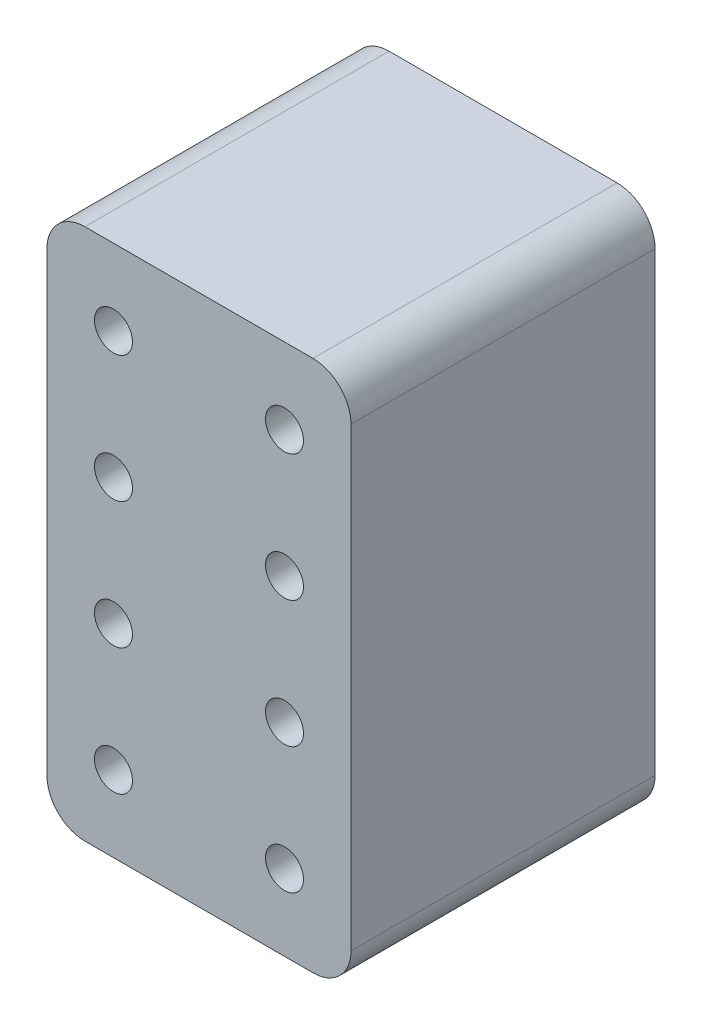
SolidWorks part; units mm, degrees
ref_plane "前视基准面" through (0, 0, 0) normal (0, 0, 1) x (1, 0, 0)
ref_plane "上视基准面" through (0, 0, 0) normal (0, 1, 0) x (1, 0, 0)
ref_plane "右视基准面" through (0, 0, 0) normal (1, 0, 0) x (0, 0, -1)
other "Configuration Table"
sketch "草图1" plane through (0, 0, 0) normal (0, 0, 1) x (1, 0, 0)
  line L0 (0, -55) -> (0, 55) construction
  line L1 (12, 28) -> (-12, 28)
  line L2 (16, 24) -> (16, -24)
  line L3 (12, -28) -> (-12, -28)
  line L4 (-16, 24) -> (-16, -24)
  line L5 (16, 28) -> (-16, -28) construction
  line L6 (16, -28) -> (-16, 28) construction
  circle A0 centre (9, 20) radius 2
  circle A1 centre (9, 6.6667) radius 2
  circle A2 centre (9, -6.6667) radius 2
  circle A3 centre (9, -20) radius 2
  circle A4 centre (-9, -20) radius 2
  circle A5 centre (-9, -6.6667) radius 2
  circle A6 centre (-9, 6.6667) radius 2
  circle A7 centre (-9, 20) radius 2
  arc A8 (-12, -28) -> (-16, -24) centre (-12, -24) cw
  arc A9 (16, -24) -> (12, -28) centre (12, -24) cw
  arc A10 (12, 28) -> (16, 24) centre (12, 24) cw
  arc A11 (-12, 28) -> (-16, 24) centre (-12, 24) ccw
  point P0 (0, 0)
  dimension "D2" = 9
  dimension "D3" = 4
  dimension "D4" = 8
  dimension "D7" = 8
  dimension "D8" = 4
  dimension "D1" = 32
  dimension "D5" = 56
  dimension "D6" = 4
extrude "凸台-拉伸1" add sketch "草图1" along normal blind 32
